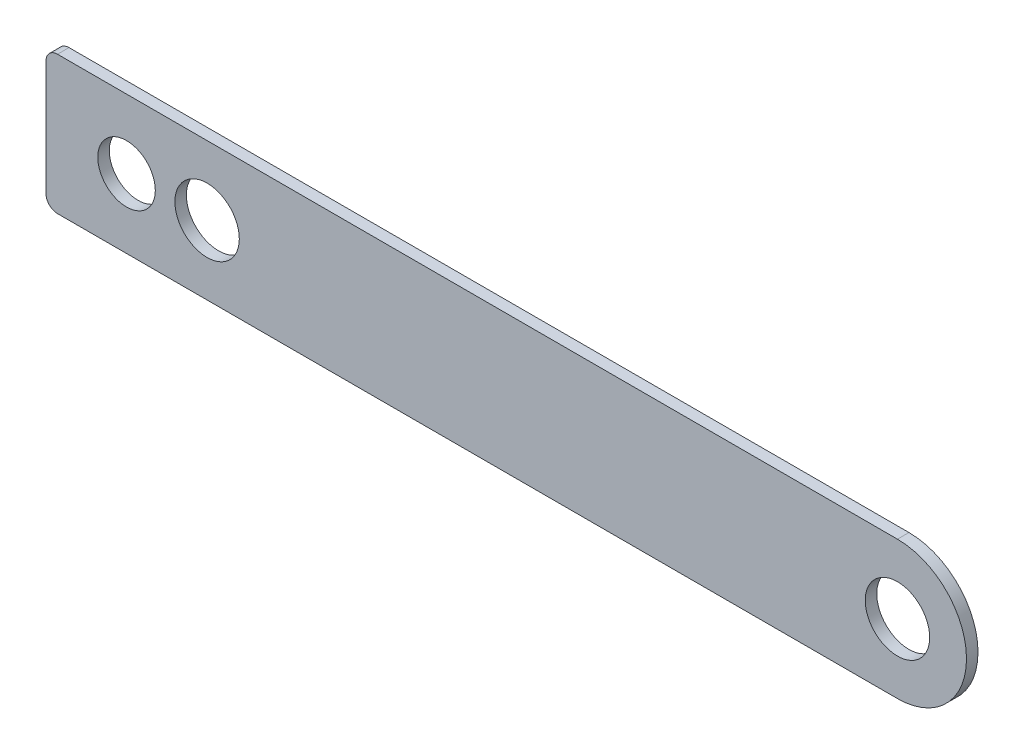
SolidWorks part; units mm, degrees
ref_plane "Alzado" through (0, 0, 0) normal (0, 0, 1) x (1, 0, 0)
ref_plane "Planta" through (0, 0, 0) normal (0, 1, 0) x (1, 0, 0)
ref_plane "Vista lateral" through (0, 0, 0) normal (1, 0, 0) x (0, 0, -1)
sketch "Croquis1" plane through (0, 0, 0) normal (0, 0, 1) x (1, 0, 0)
  line L0 (400, 60) -> (370, 60) construction
  line L1 (5, 0) -> (370, 0)
  line L2 (0, 5) -> (0, 55)
  line L3 (5, 60) -> (370, 60)
  arc A0 (370, 60) -> (370, 0) centre (370, 30) cw
  arc A1 (5, 0) -> (0, 5) centre (5, 5) cw
  arc A2 (0, 55) -> (5, 60) centre (5, 55) cw
  point P3 (400, 30)
  point P10 (0, 0)
  point P13 (0, 60)
  dimension "D4" = 5
  dimension "D1" = 400
  dimension "D2" = 60
  dimension "D3" = 30
extrude "Saliente-Extruir1" add sketch "Croquis1" along normal blind 5
sketch "Croquis2" plane through (0, 0, 5) normal (0, 0, 1) x (1, 0, 0)
  line L0 (370, 60) -> (370, 0) construction
  line L1 (0, 30) -> (35, 30) construction
  line L2 (0, 55) -> (0, 5) construction
  line L3 (35, 30) -> (70, 30) construction
  circle A0 centre (370, 30) radius 14
  circle A1 centre (35, 30) radius 12.5
  circle A2 centre (70, 30) radius 14
  dimension "D1" = 28
  dimension "D3" = 25
  dimension "D5" = 28
  dimension "D2" = 35
  dimension "D4" = 35
extrude "Cortar-Extruir1" cut sketch "Croquis2" against normal blind 5 contours A1 | A0 | A2
